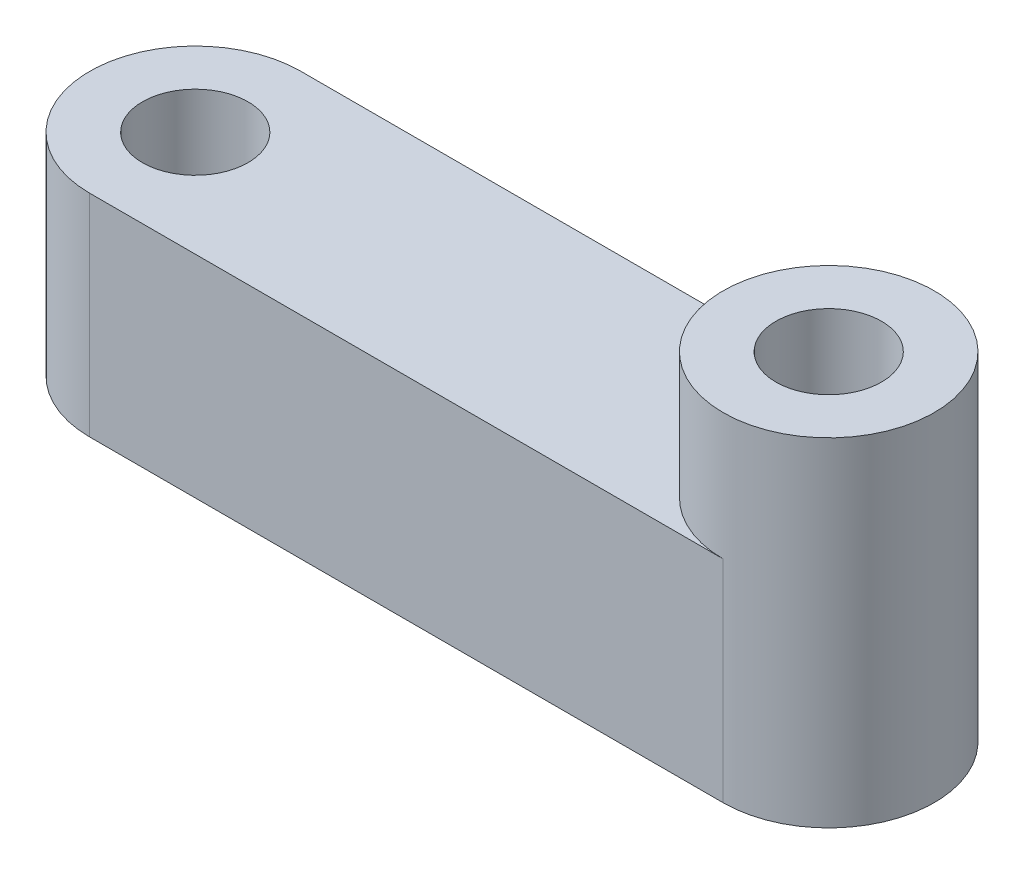
SolidWorks part; units mm, degrees
ref_plane "Front Plane" through (0, 0, 0) normal (0, 0, 1) x (1, 0, 0)
ref_plane "Top Plane" through (0, 0, 0) normal (0, 1, 0) x (1, 0, 0)
ref_plane "Right Plane" through (0, 0, 0) normal (1, 0, 0) x (0, 0, -1)
sketch "Sketch1" plane through (0, 0, 0) normal (0, 1, 0) x (1, 0, 0)
  line L0 (0, 0) -> (30, 0) construction
  line L1 (0, 5) -> (30, 5)
  line L2 (0, -5) -> (30, -5)
  arc A0 (0, 5) -> (0, -5) centre (0, 0) ccw
  arc A1 (30, -5) -> (30, 5) centre (30, 0) ccw
  circle A2 centre (0, 0) radius 2.5
  circle A3 centre (30, 0) radius 2.5
  point P3 (15, 0)
  dimension "D3" = 5
  dimension "D4" = 5
  dimension "D1" = 30
  dimension "D2" = 10
extrude "Boss-Extrude1" add sketch "Sketch1" along normal blind 4 and the other way blind 6
ref_plane "Plane1" through (0, -1, 0) normal (0, 1, 0) x (1, 0, 0)
sketch "Sketch3" plane through (0, -1, 0) normal (0, 1, 0) x (1, 0, 0)
  circle A0 centre (30, 0) radius 5
  circle A1 centre (30, 0) radius 2.5
extrude "Boss-Extrude3" add sketch "Sketch3" along normal blind 11 and the other way blind 5
sketch "Sketch4" plane through (0, 4, 0) normal (0, 1, 0) x (1, 0, 0)
  line L0 (15, 5) -> (15, 0) construction
  line L1 (30, 5) -> (0, 5) construction
  line L3 (10.8195, 0) -> (18.4441, 0) construction
  line L4 (12.0283, 2.5) -> (17.5608, 2.5) construction
  line L5 (15, 0) -> (15, -5) construction
  line L6 (0, -5) -> (30, -5) construction
  line L7 (12.0283, -2.5) -> (17.5608, -2.5) construction
  line L8 (0, -5) -> (30, -5)
  line L9 (0, 5) -> (30, 5)
  arc A0 (2.7717, 4.1615) -> (0, 5) centre (0, 0) ccw
  arc A1 (33.7733, -3.2805) -> (30, -5) centre (30, 0) ccw
  arc A2 (0, -5) -> (2.7717, -4.1615) centre (0, 0) ccw
  arc A3 (30, 5) -> (33.7733, 3.2805) centre (30, 0) ccw
  spline S0 degree 3 poles (2.7717, 4.1615) (6.8478, 3.0538) (11.7275, 2.3866) (29.6972, 2.1729) (33.7733, 3.2805) knots 0.092389 0.092389 0.092389 0.092389 0.5 0.907611 0.907611 0.907611 0.907611
  spline S1 degree 3 poles (2.7717, -4.1615) (6.8478, -3.0538) (11.7275, -2.3866) (29.6972, -2.1729) (33.7733, -3.2805) knots 0.092389 0.092389 0.092389 0.092389 0.5 0.907611 0.907611 0.907611 0.907611
